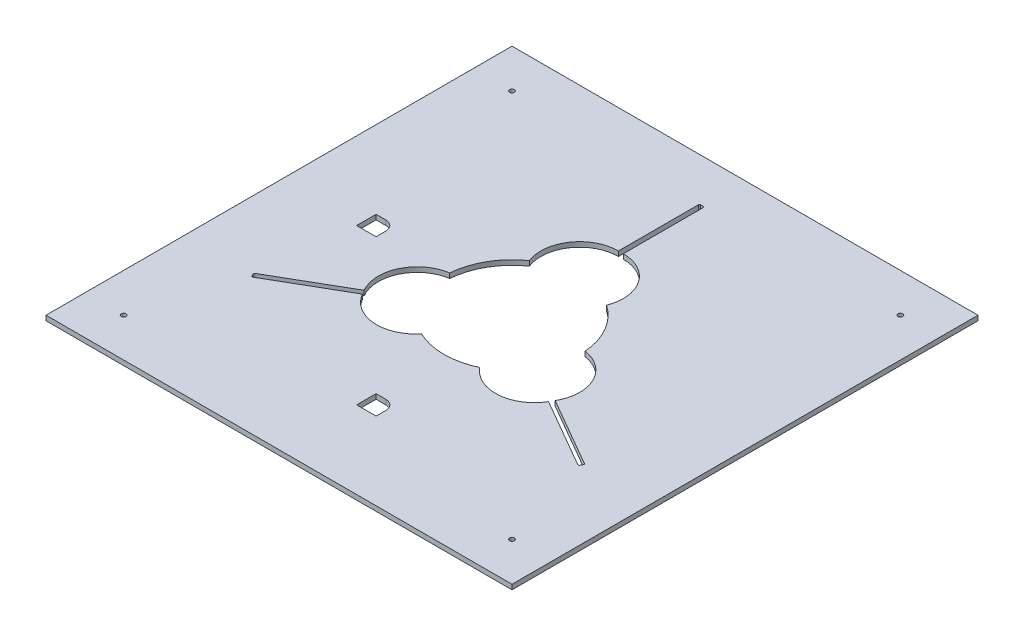
SolidWorks part; units mm, degrees
ref_plane "Front Plane" through (0, 0, 0) normal (0, 0, 1) x (1, 0, 0)
ref_plane "Top Plane" through (0, 0, 0) normal (0, 1, 0) x (1, 0, 0)
ref_plane "Right Plane" through (0, 0, 0) normal (1, 0, 0) x (0, 0, -1)
sketch "Sketch1" plane through (0, 0, 0) normal (0, 1, 0) x (1, 0, 0)
  line L1 (-304.8, -304.8) -> (304.8, -304.8)
  line L2 (-304.8, -304.8) -> (-304.8, 304.8)
  line L3 (-304.8, 304.8) -> (304.8, 304.8)
  line L4 (304.8, -304.8) -> (304.8, 304.8)
  line L5 (0, 304.8) -> (0, -304.8) construction
  line L6 (-304.8, 0) -> (304.8, 0) construction
  point P0 (0, 0)
  dimension "D1" = 609.6
  dimension "D2" = 609.6
extrude "Boss-Extrude1" add sketch "Sketch1" along normal blind 6.35 contours L2 L3 L4 L1
sketch "Sketch3" plane through (0, 0, 0) normal (0, 1, 0) x (1, 0, 0)
  line L0 (0, 0) -> (0, 332.7806) construction
  line L1 (0, 0) -> (-286.8222, -165.5969) construction
  line L2 (0, 0) -> (289.9079, -167.3784) construction
  line L3 (-3.175, 248.4755) -> (-3.175, 142.4547)
  line L4 (-50.4923, 73.1692) -> (50.4923, 73.1692) construction
  line L5 (-3.175, 248.4755) -> (3.175, 248.4755)
  line L6 (213.5986, -126.9874) -> (121.7819, -73.977)
  line L7 (3.175, 248.4755) -> (3.175, 142.4547)
  line L8 (216.7736, -121.4881) -> (124.9569, -68.4777)
  line L9 (216.7736, -121.4881) -> (213.5986, -126.9874)
  line L10 (-216.7736, -121.4881) -> (-124.9569, -68.4777)
  line L11 (-213.5986, -126.9874) -> (-121.7819, -73.977)
  line L12 (-213.5986, -126.9874) -> (-216.7736, -121.4881)
  line L20 (-3.175, 142.4547) -> (3.175, 142.4547) construction
  arc A0 (88.6126, 7.143) -> (50.4923, 73.1692) centre (0, 0) ccw
  arc A1 (-3.175, 142.4547) -> (-50.4923, 73.1692) centre (-3.175, 91.6547) ccw
  arc A2 (3.175, 142.4547) -> (50.4923, 73.1692) centre (3.175, 91.6547) cw
  arc A3 (-50.4923, 73.1692) -> (-88.6126, 7.143) centre (0, 0) ccw
  arc A4 (121.7819, -73.977) -> (38.1203, -80.3122) centre (77.7878, -48.577) cw
  arc A5 (124.9569, -68.4777) -> (88.6126, 7.143) centre (80.9628, -43.0777) ccw
  arc A6 (-38.1203, -80.3122) -> (38.1203, -80.3122) centre (0, 0) ccw
  arc A7 (-124.9569, -68.4777) -> (-88.6126, 7.143) centre (-80.9628, -43.0777) cw
  arc A8 (-121.7819, -73.977) -> (-38.1203, -80.3122) centre (-77.7878, -48.577) ccw
  point P3 (0, 169.3508)
  point P17 (0, 83.82)
  point P33 (0, 0)
  point P34 (0, 0)
  point P37 (0, 0)
  point P62 (0, 0)
  dimension "D6" = 88.9
  dimension "D7" = 50.8
  dimension "D11" = 6.35
  dimension "D16" = 83.82
  dimension "D10" = 100.9846
  dimension "D2" = 120
  dimension "D3" = 120
  dimension "D4" = 6.35
  dimension "D5" = 164.6555
  dimension "D8" = 3
extrude "Cut-Extrude2" cut sketch "Sketch3" along normal through all
sketch "Sketch4" plane through (0, 0, 0) normal (0, 1, 0) x (1, 0, 0)
  line L0 (0, 0) -> (-203.2, 0) construction
  line L1 (0, 0) -> (0, -203.2) construction
  line L3 (0, -203.2) -> (25.4, -203.2)
  line L4 (0, -203.2) -> (0, -177.8)
  line L5 (0, -177.8) -> (25.4, -177.8)
  line L6 (25.4, -203.2) -> (25.4, -177.8)
  line L7 (-203.2, 0) -> (-177.8, 0)
  line L8 (-203.2, 0) -> (-203.2, 25.4)
  line L9 (-203.2, 25.4) -> (-177.8, 25.4)
  line L10 (-177.8, 0) -> (-177.8, 25.4)
  dimension "D1" = 203.2
  dimension "D2" = 203.2
  dimension "D3" = 25.4
  dimension "D4" = 25.4
  dimension "D5" = 25.4
  dimension "D6" = 25.4
extrude "Cut-Extrude8" cut sketch "Sketch4" along normal through all
fillet "Fillet4" radius 12.7 1 edges at (-177.8, 3.175, -25.4)
fillet "Fillet5" radius 12.7 1 edges at (25.4, 3.175, 177.8)
sketch "Sketch5" plane through (0, 6.35, 0) normal (0, 1, 0) x (1, 0, 0)
  line L1 (-254, -254) -> (254, -254) construction
  line L2 (-254, -254) -> (-254, 254) construction
  line L3 (-254, 254) -> (254, 254) construction
  line L4 (254, -254) -> (254, 254) construction
  line L5 (0, 254) -> (0, -254) construction
  line L6 (-254, 0) -> (254, 0) construction
  circle A0 centre (-254, 254) radius 3.175
  circle A1 centre (254, 254) radius 3.175
  circle A2 centre (254, -254) radius 3.175
  circle A3 centre (-254, -254) radius 3.175
  point P0 (0, 0)
  dimension "D3" = 6.35
  dimension "D1" = 508
  dimension "D2" = 508
  dimension "D4" = 2
  dimension "D5" = 2
extrude "Cut-Extrude9" cut sketch "Sketch5" against normal through all
fillet "Fillet9" radius 1.5875 6 edges at (216.7736, 3.175, 121.4881) (213.5986, 3.175, 126.9874) (-216.7736, 3.175, 121.4881) (-213.5986, 3.175, 126.9874) (3.175, 3.175, -248.4755) (-3.175, 3.175, -248.4755)
